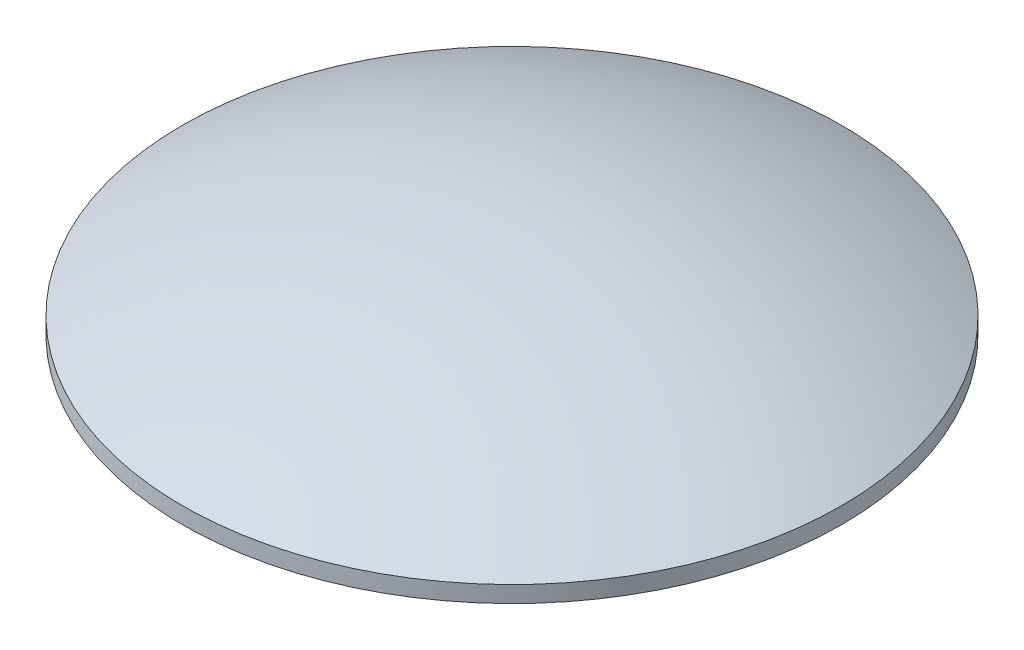
SolidWorks part; units mm, degrees
material "ABS"
ref_plane "Front Plane" through (0, 0, 0) normal (0, 0, 1) x (1, 0, 0)
ref_plane "Top Plane" through (0, 0, 0) normal (0, 1, 0) x (1, 0, 0)
ref_plane "Right Plane" through (0, 0, 0) normal (1, 0, 0) x (0, 0, -1)
sketch "Sketch1" plane through (0, 0, 0) normal (0, 0, 1) x (1, 0, 0)
  line L0 (0, 0) -> (20, 0)
  line L1 (20, 0) -> (20, 1)
  line L2 (20, 1) -> (-20, 1) construction
  line L3 (0, 1) -> (0, 0)
  line L4 (0, 6) -> (0, 5)
  line L5 (17.7764, 1) -> (0, 1)
  arc A0 (-20, 1) -> (20, 1) centre (0, -36.5) cw
  arc A1 (0, 5) -> (17.7764, 1) centre (0, -36.5) cw
  dimension "D1" = 1
  dimension "D2" = 1
  dimension "D3" = 20
  dimension "D4" = 6
revolve "Revolve1" add sketch "Sketch1" angle 360 about L3
sketch "Sketch2" plane through (0, 1, 0) normal (0, 1, 0) x (1, 0, 0)
  circle A0 centre (0, -3.7764) radius 14
  circle A1 centre (0, 0) radius 17.7764 construction
  dimension "D1" = 28
extrude "Boss-Extrude1" add sketch "Sketch2" along normal blind 1 separate body
